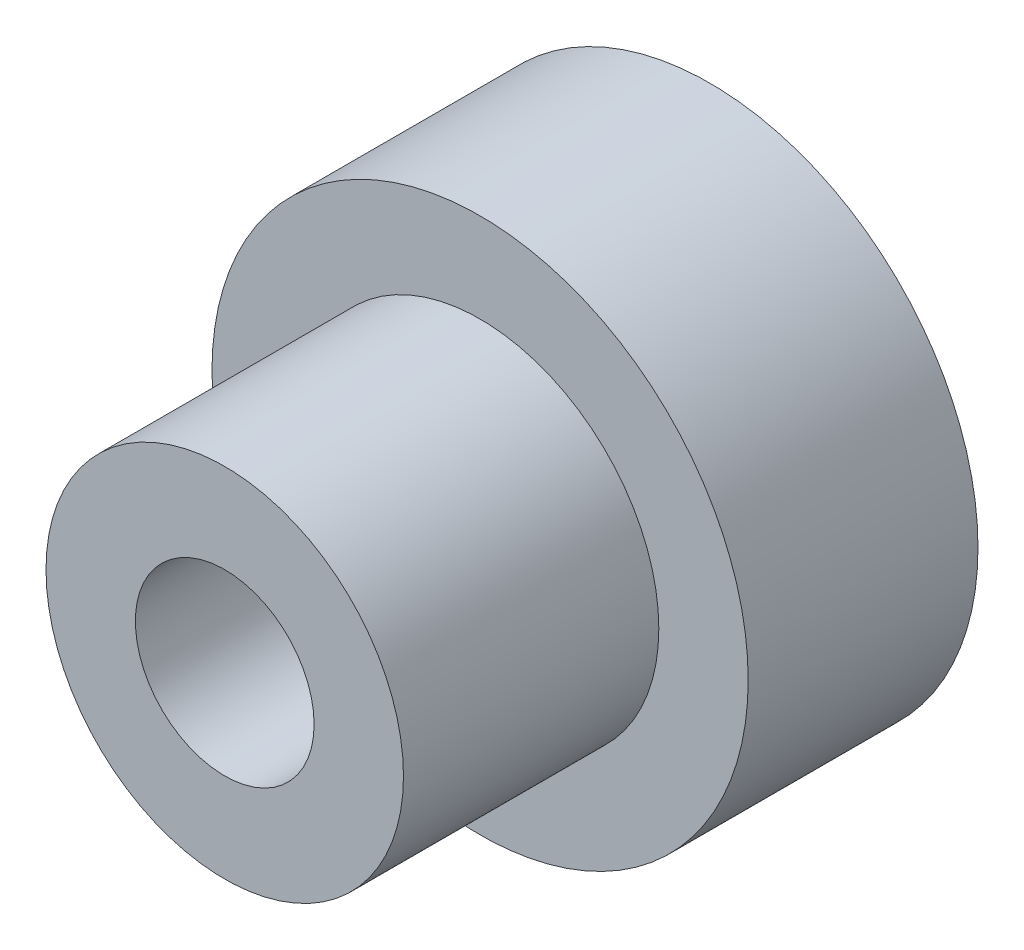
SolidWorks part; units mm, degrees
material "Фторопласт-4 ГОСТ 10007-80 Е"
ref_plane "Спереди" through (0, 0, 0) normal (0, 0, 1) x (1, 0, 0)
ref_plane "Сверху" through (0, 0, 0) normal (0, 1, 0) x (1, 0, 0)
ref_plane "Справа" through (0, 0, 0) normal (1, 0, 0) x (0, 0, -1)
sketch "Эскиз2" plane through (0, 0, 0) normal (0, 0, 1) x (1, 0, 0)
  circle A0 centre (0, 0) radius 7
  dimension "D1" = 14
extrude "Бобышка-Вытянуть1" add sketch "Эскиз2" along normal blind 10
sketch "Эскиз3" plane through (0, 0, 0) normal (0, 0, -1) x (-1, 0, 0)
  circle A0 centre (0, 0) radius 10.5
  dimension "D1" = 21
extrude "Бобышка-Вытянуть2" add sketch "Эскиз3" along normal blind 9
sketch "Эскиз4" plane through (0, 0, 10) normal (0, 0, 1) x (1, 0, 0)
  circle A0 centre (0, 0) radius 3.5
  dimension "D1" = 7
extrude "Вырез-Вытянуть1" cut sketch "Эскиз4" against normal through all
sketch "Эскиз5" plane through (0, 0, 10) normal (0, 0, 1) x (1, 0, 0)
  circle A0 centre (0, 0) radius 5.5
  dimension "D1" = 11
extrude "Вырез-Вытянуть2" cut sketch "Эскиз5" against normal blind 2.5 from offset 13
